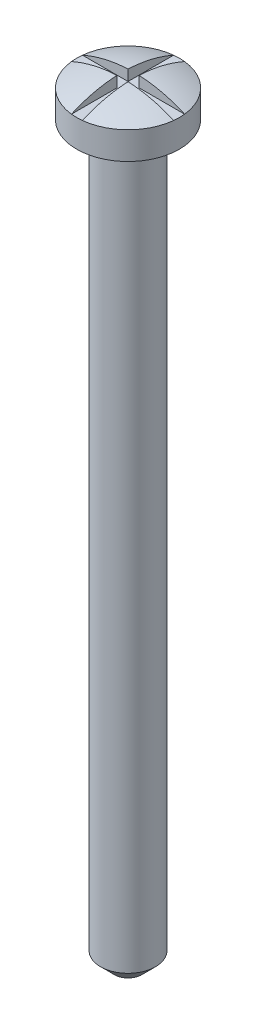
SolidWorks part; units mm, degrees
material "1023 Arkusz stali węglowej (SS)"
ref_plane "Płaszczyzna przednia" through (0, 0, 0) normal (0, 0, 1) x (1, 0, 0)
ref_plane "Płaszczyzna górna" through (0, 0, 0) normal (0, 1, 0) x (1, 0, 0)
ref_plane "Płaszczyzna prawa" through (0, 0, 0) normal (1, 0, 0) x (0, 0, -1)
sketch "Szkic1" plane through (0, 0, 0) normal (0, 0, 1) x (1, 0, 0)
  line L0 (0, 0) -> (0, 42.1) construction
  line L1 (0, 0) -> (-1.5, 0)
  line L2 (-1.5, 0) -> (-1.5, 40)
  line L3 (-1.5, 40) -> (-2.8, 40)
  line L4 (-2.8, 40) -> (-2.8, 41.5)
  line L5 (0, 42.1) -> (-17.8028, 42.1) construction
  line L6 (0, 0) -> (0, 42.1)
  arc A0 (0, 42.1) -> (-2.8, 41.5) centre (0, 35.2667) ccw
  dimension "D1" = 40
  dimension "D2" = 1.5
  dimension "D3" = 2.8
  dimension "D4" = 2.1
  dimension "D5" = 1.5
revolve "Obrót1" add sketch "Szkic1" angle 360 about L6
sketch "Szkic2" plane through (0, 40, 0) normal (0, -1, 0) x (1, 0, 0)
  line L1 (-0.3, 2.8) -> (0.3, 2.8)
  line L2 (-0.3, 2.8) -> (-0.3, -2.8)
  line L3 (-0.3, -2.8) -> (0.3, -2.8)
  line L4 (0.3, 2.8) -> (0.3, -2.8)
  line L5 (0, -2.8) -> (0, 2.8) construction
  line L6 (-0.3, 0) -> (0.3, 0) construction
  line L7 (-2.8, -0.3) -> (2.8, -0.3)
  line L8 (-2.8, -0.3) -> (-2.8, 0.3)
  line L9 (-2.8, 0.3) -> (2.8, 0.3)
  line L10 (2.8, -0.3) -> (2.8, 0.3)
  line L11 (0, 0.3) -> (0, -0.3) construction
  line L12 (-2.8, 0) -> (2.8, 0) construction
  circle A0 centre (0, 0) radius 2.8 construction
  point P0 (0, 0)
  point P4 (0, 0)
  circle M5 centre (0, 0) radius 1.5
  circle M6 centre (0, 0) radius 2.8
  dimension "D1" = 0.6
extrude "Wytnij-wyciągnięcie1" cut sketch "Szkic2" along normal blind 3.5 from offset 5 contours L7 L2 L4 M5 | L9 L7 L2 M5 | L2 L9 L4 M5 | L4 L2 M6 M5 | L9 L7 M6 M5 | L4 L2 M5 M6 | L9 L7 M5 M6 | L9 L4 L7 M5 | L9 L2 L7 L4 offset against normal yes
chamfer "Sfazowanie1" distance 0.75 angle 45 1 edges at (1.5, 0, 0)
